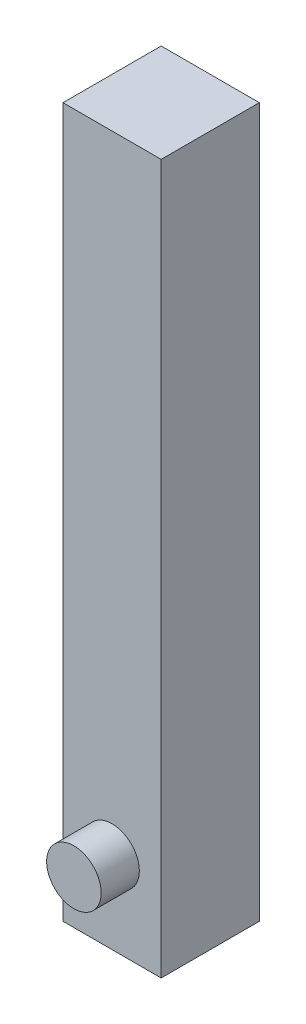
SolidWorks part; units mm, degrees
ref_plane "Front Plane" through (0, 0, 0) normal (1, 0, 0) x (0, 1, 0)
ref_plane "Top Plane" through (0, 0, 0) normal (0, 0, 1) x (0, 1, 0)
ref_plane "Right Plane" through (0, 0, 0) normal (0, 1, 0) x (-1, 0, 0)
sketch "Sketch1" plane through (0, 0, 0) normal (0, 0, 1) x (0, 1, 0)
  line L1 (-32.5, -4.5) -> (32.5, -4.5)
  line L2 (-32.5, -4.5) -> (-32.5, 4.5)
  line L3 (-32.5, 4.5) -> (32.5, 4.5)
  line L4 (32.5, -4.5) -> (32.5, 4.5)
  line L5 (-32.5, -4.5) -> (32.5, 4.5) construction
  line L6 (-32.5, 4.5) -> (32.5, -4.5) construction
  point P0 (0, 0)
  dimension "D1" = 9
  dimension "D2" = 65
extrude "Boss-Extrude1" add sketch "Sketch1" along normal mid plane 12.5
sketch "Sketch2" plane through (0, 0, 6.25) normal (0, 0, 1) x (1, 0, 0)
  circle A0 centre (0, 25) radius 2.5
  circle A1 centre (0, -25) radius 2.5
  line M3 (4.5, 32.5) -> (-4.5, 32.5)
  line M4 (-4.5, 32.5) -> (-4.5, -32.5)
  line M5 (-4.5, -32.5) -> (4.5, -32.5)
  line M6 (4.5, -32.5) -> (4.5, 32.5)
  dimension "D3" = 5
  dimension "D1" = 50
  dimension "D2" = 25
extrude "Cut-Extrude1" [suppressed] cut sketch "Sketch2" against normal blind 3.5 contours A1 A0 M6 M3 M4 M5
sketch "Sketch3" plane through (0, 0, 6.25) normal (0, 0, 1) x (1, 0, 0)
  circle A0 centre (0, -25) radius 2.5
  line M2 (4.5, 32.5) -> (-4.5, 32.5)
  line M3 (-4.5, 32.5) -> (-4.5, -32.5)
  line M4 (-4.5, -32.5) -> (4.5, -32.5)
  line M5 (4.5, -32.5) -> (4.5, 32.5)
  dimension "D1" = 5
  dimension "D2" = 25
extrude "Cut-Extrude2" cut sketch "Sketch3" against normal blind 3.5 contours A0 M5 M2 M3 M4
